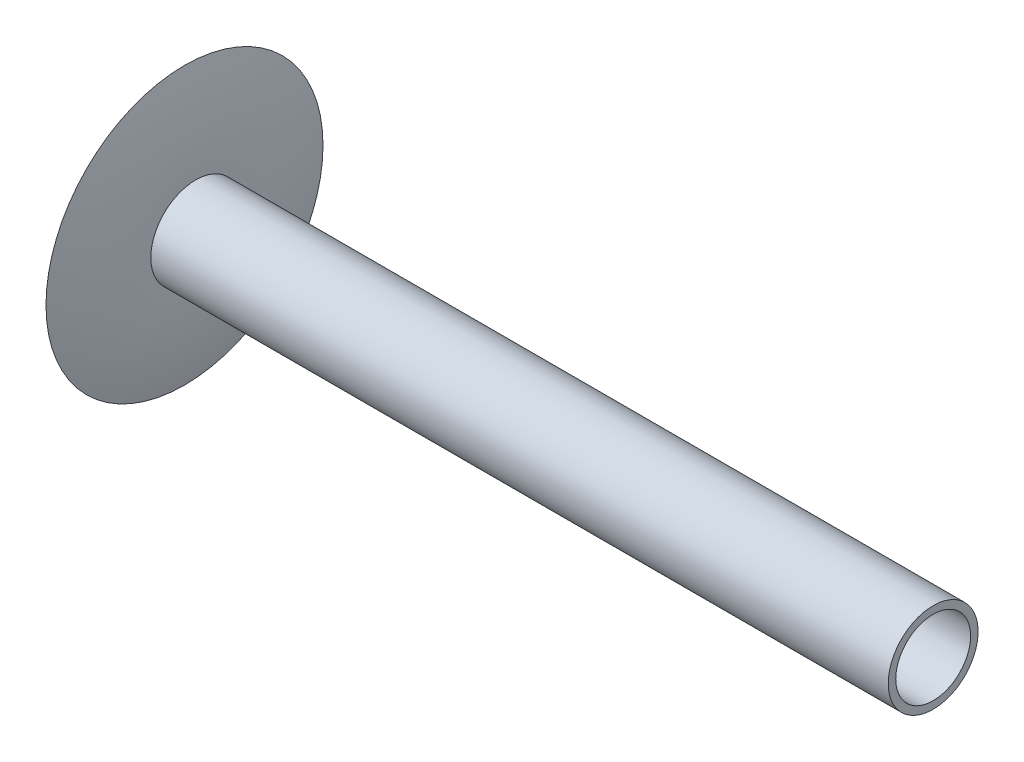
SolidWorks part; units mm, degrees
material "Zinc AC41A Alloy, As Cast"
ref_plane "Front Plane" through (0, 0, 0) normal (0, 0, 1) x (1, 0, 0)
ref_plane "Top Plane" through (0, 0, 0) normal (0, 1, 0) x (1, 0, 0)
ref_plane "Right Plane" through (0, 0, 0) normal (1, 0, 0) x (0, 0, -1)
sketch "Sketch1" plane through (0, 0, 0) normal (0, 0, 1) x (1, 0, 0)
  line L0 (0, 0) -> (200, 0) construction
  line L1 (0, -10) -> (0, -37)
  line L2 (0, -10) -> (200, -10)
  line L3 (0, -10) -> (0, -12)
  line L4 (0, -12) -> (200, -12)
  line L5 (200, -10) -> (200, -12)
  line L6 (0, -12) -> (3, -12)
  arc A0 (3, -12) -> (0, -37) centre (-92.7594, -13.1889) cw
  dimension "D1" = 200
  dimension "D2" = 2
  dimension "D3" = 10
  dimension "D4" = 27
  dimension "D5" = 3
revolve "Revolve1" add sketch "Sketch1" angle 360 about L0
